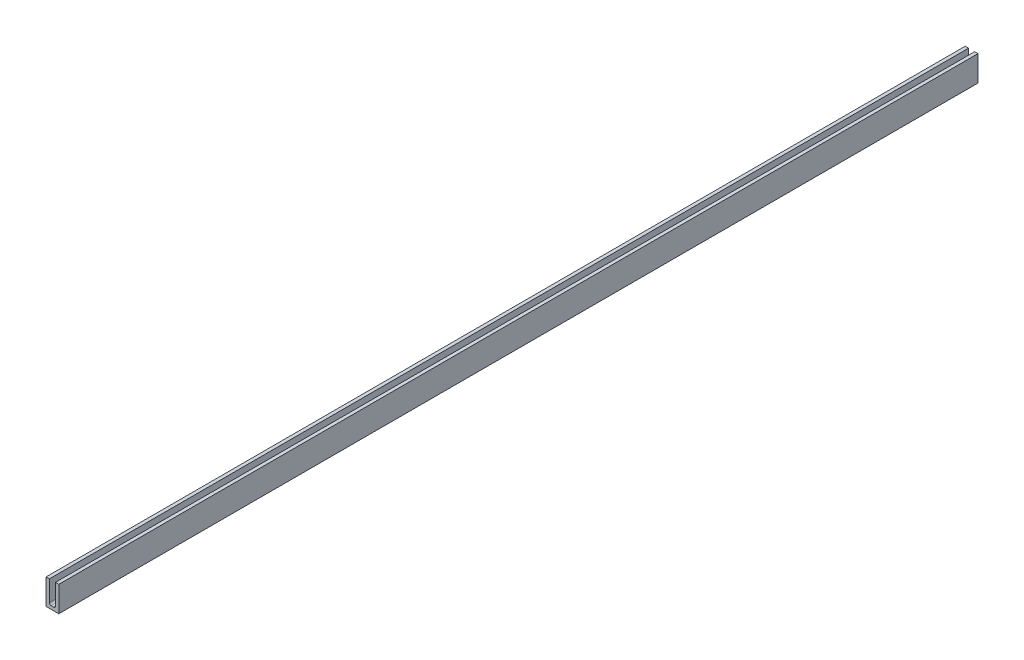
SolidWorks part; units mm, degrees
ref_plane "Front Plane" through (0, 0, 0) normal (0, 0, 1) x (1, 0, 0)
ref_plane "Top Plane" through (0, 0, 0) normal (0, 1, 0) x (1, 0, 0)
ref_plane "Right Plane" through (0, 0, 0) normal (1, 0, 0) x (0, 0, -1)
sketch "Sketch1" plane through (0, 0, 0) normal (0, 0, 1) x (1, 0, 0)
  line L0 (-6.35, 12.7) -> (-6.35, -12.7) construction
  line L1 (-6.35, -12.7) -> (6.35, -12.7) construction
  line L2 (6.35, -12.7) -> (6.35, 12.7) construction
  line L3 (3.048, -9.398) -> (-3.048, -9.398) construction
  line L4 (-3.048, -9.398) -> (-3.048, 12.7) construction
  line L6 (-3.048, 12.7) -> (-6.35, 12.7) construction
  line L7 (0, -12.7) -> (0, 0) construction
  line L8 (6.35, 12.7) -> (3.048, 12.7) construction
  line L9 (3.048, 12.7) -> (3.048, -9.398) construction
  line L10 (0, -9.398) -> (0, -12.7) construction
  point P4 (0, 0)
  point P11 (6.35, -9.398)
  dimension "D1" = 12.7
  dimension "Outside Height" = 25.4
  dimension "Outside Width" = 12.7
  dimension "Leg Thickness" = 3.302
  dimension "Inside Height" = 22.098
  dimension "Inside Width" = 6.096
  dimension "Base Thickness" = 3.302
sketch "Sketch2" plane through (0, 0, 0) normal (1, 0, 0) x (0, 0, -1)
  line L0 (457.2, 12.7) -> (-457.2, 12.7) construction
  line L1 (0, -9.398) -> (0, 12.7) construction
  point P0 (-444.5, 12.7)
  point P4 (0, 12.7)
  point P6 (444.5, 12.7)
  dimension "D1" = 12.7
  dimension "D2" = 12.7
  dimension "Length" = 914.4
sketch "Sketch3" plane through (0, 0, 0) normal (0, 0, 1) x (1, 0, 0)
  line L6 (-6.35, 12.7) -> (-6.35, -12.7)
  line L7 (-6.35, -12.7) -> (6.35, -12.7)
  line L8 (6.35, -12.7) -> (6.35, 12.7)
  line L9 (6.35, 12.7) -> (3.048, 12.7)
  line L10 (3.048, 12.7) -> (3.048, -9.398)
  line L11 (3.048, -9.398) -> (-3.048, -9.398)
  line L12 (-3.048, -9.398) -> (-3.048, 12.7)
  line L13 (-3.048, 12.7) -> (-6.35, 12.7)
extrude "Boss-Extrude1" add sketch "Sketch3" along normal mid plane 914.4
fillet "Fillet1" radius 1.651 2 edges at (3.048, -9.398, 0) (-3.048, -9.398, 0)
equation "\"D1@Boss-Extrude1\"=\"Length@Sketch2\""
equation "\"D2@Sketch2\"=\"D1@Sketch2\""
equation "\"D1@Sketch1\"=\"Outside Height@Sketch1\"/2"
equation "\"D1@Fillet1\"=\"Leg Thickness@Sketch1\"*.5"
equation "\"D1@Sketch2\"=\"Outside Width@Sketch1\"*1"
